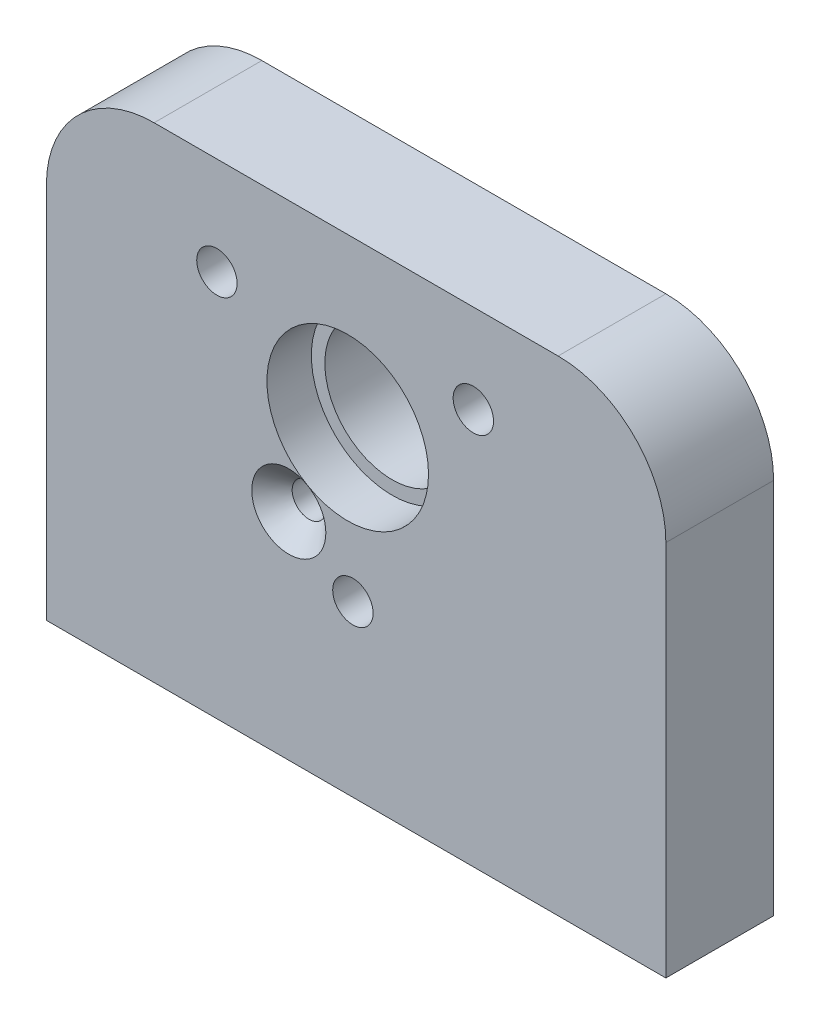
SolidWorks part; units mm, degrees
material "ABS"
ref_plane "Front Plane" through (0, 0, 0) normal (0, 0, 1) x (1, 0, 0)
ref_plane "Top Plane" through (0, 0, 0) normal (0, 1, 0) x (1, 0, 0)
ref_plane "Right Plane" through (0, 0, 0) normal (1, 0, 0) x (0, 0, -1)
ref_plane "Plane1" through (0, 0, 4.5) normal (0, 0, 1) x (1, 0, 0)
sketch "Sketch1" plane through (0, 0, 4.5) normal (0, 0, 1) x (1, 0, 0)
  line L0 (23, -18) -> (23, 18)
  line L1 (23, 18) -> (-23, 18)
  line L2 (-23, 18) -> (-23, -18)
  line L3 (-23, -18) -> (23, -18)
extrude "Boss-Extrude1" add sketch "Sketch1" against normal blind 8
ref_plane "Plane2" through (0, -2, 0) normal (0, 1, 0) x (1, 0, 0)
hole_wizard "Ø3.0mm Dowel Hole1" positions "Sketch6" profile "Sketch5" hole size "Ø3.0" standard "ANSI Metric"
sketch "Sketch6" plane through (0, -18, 0) normal (0, -1, 0) x (-1, 0, 0)
  line L0 (23, -4.5) -> (-23, -4.5) construction
  point P0 (0, -0.5)
  dimension "D1" = 4
sketch "Sketch5" plane through (0, -18, 0.5) normal (1, 0, 0) x (0, 0, -1)
  line L0 (0, 0) -> (0, 9.4013)
  line L1 (0, 9.4013) -> (1.5, 8.5)
  line L2 (1.5, 8.5) -> (1.5, 0)
  line L5 (1.5, 0) -> (0, 0)
  line L10 (0, 9.4013) -> (-1.5, 8.5) construction
  line L11 (0, -6.35) -> (0, 107.95) construction
  dimension "Hole Dia." = 3
  dimension "Hole Depth" = 8.5
  dimension "Drill Angle" = 118
hole_wizard "Ø4.0mm Dowel Hole1" positions "Sketch8" profile "Sketch7" hole size "Ø4.0" standard "ANSI Metric"
sketch "Sketch8" plane through (0, -18, 0) normal (0, -1, 0) x (-1, 0, 0)
  line L0 (23, -4.5) -> (-23, -4.5) construction
  point P0 (19, -0.5)
  point P1 (-19, -0.5)
  dimension "D1" = 4
sketch "Sketch7" plane through (-19, -18, 0.5) normal (1, 0, 0) x (0, 0, -1)
  line L0 (0, 0) -> (0, 8.7017)
  line L1 (0, 8.7017) -> (2, 7.5)
  line L2 (2, 7.5) -> (2, 0)
  line L5 (2, 0) -> (0, 0)
  line L10 (0, 8.7017) -> (-2, 7.5) construction
  line L11 (0, -6.35) -> (0, 107.95) construction
  dimension "Hole Dia." = 4
  dimension "Hole Depth" = 7.5
  dimension "Drill Angle" = 118
fillet "Fillet2" radius 8 2 edges at (23, 18, 0.5) (-23, 18, 0.5)
sketch "Sketch16" plane through (0, 0, -3.5) normal (0, 0, -1) x (-1, 0, 0)
  line L0 (23, -18) -> (-23, -18) construction
  line L1 (2.5, -4.5) -> (7.5, -4.5)
  line L2 (2.5, -4.5) -> (2.5, 0.5)
  line L3 (2.5, 0.5) -> (7.5, 0.5)
  line L4 (7.5, -4.5) -> (7.5, 0.5)
  line L5 (2.5, -4.5) -> (7.5, 0.5) construction
  line L6 (2.5, 0.5) -> (7.5, -4.5) construction
  line L9 (23, 10) -> (23, -18) construction
  point P0 (5, -2)
  dimension "D1" = 16
  dimension "D2" = 18
  dimension "D3" = 5
extrude "Cut-Extrude1" cut sketch "Sketch16" against normal blind 4.5
hole_wizard "CSK for M2.5 Flat Head Machine Screw1" positions "3DSketch1" profile "Sketch17" countersink size "M2.5" standard "ANSI Metric"
sketch3d "3DSketch1"
  line L0 (-23, -18, 4.5) -> (23, -18, 4.5) construction
  line L1 (-23, 10, 4.5) -> (-23, -18, 4.5) construction
  point P0 (-5, -2, 4.5)
  dimension "D1" = 16
  dimension "D2" = 18
sketch "Sketch17" plane through (-5, -2, 4.5) normal (1, 0, 0) x (0, -1, 0)
  line L0 (0, 0) -> (0, 10.2511)
  line L1 (0, 10.2511) -> (1.25, 9.5)
  line L2 (1.25, 9.5) -> (1.25, 1.5)
  line L3 (1.25, 1.5) -> (2.75, 0)
  line L5 (2.75, 0) -> (0, 0)
  line L6 (-1.25, 1.5) -> (-2.75, 0) construction
  line L10 (0, 10.2511) -> (-1.25, 9.5) construction
  line L11 (0, -6.35) -> (0, 107.95) construction
  dimension "Hole Dia." = 2.5
  dimension "Hole Depth" = 9.5
  dimension "Near C'Sink Dia." = 5.5
  dimension "Near C'Sink Angle" = 90
  dimension "Drill Angle" = 118
hole_wizard "Hole1" positions "Sketch12" profile "Sketch11" legacy end condition through all
sketch "Sketch12" plane through (0, 0, 4.5) normal (0, 0, 1) x (1, 0, 0)
  line L0 (-5, -2) -> (-0.625, 5.5777) construction
  line L1 (-0.625, 5.5777) -> (-0.625, -18) construction
  line L2 (-23, -18) -> (23, -18) construction
  point P0 (-0.625, 5.5777)
  dimension "D1" = 8.75
  dimension "D2" = 30
sketch "Sketch11" plane through (-0.625, 5.5777, 4.5) normal (1, 0, 0) x (0, -1, 0)
  line L0 (0, 0) -> (0, 8)
  line L1 (0, 8) -> (5, 8)
  line L2 (5, 8) -> (5, 3.3)
  line L3 (5, 3.3) -> (6, 3.3)
  line L4 (6, 3.3) -> (6, 0)
  line L5 (6, 0) -> (0, 0)
  line L6 (0, 110) -> (0, -10) construction
  dimension "Diameter" = 10
  dimension "Depth" = 8
  dimension "C-Bore Diameter" = 12
  dimension "C-Bore Depth" = 3.3
hole_wizard "Ø3.0 (3) Diameter Hole1" positions "Sketch10" profile "Sketch9" hole size "Ø3.0" standard "ANSI Metric" end condition through all
sketch "Sketch10" plane through (0, 0, -3.5) normal (0, 0, -1) x (-1, 0, 0)
  line L1 (10.3374, 10.7419) -> (-8.7035, 11.4068) construction
  line L2 (-8.7035, 11.4068) -> (0.2411, -5.4156) construction
  line L3 (0.2411, -5.4156) -> (10.3374, 10.7419) construction
  line L4 (0.625, 5.5777) -> (0.2411, -5.4156) construction
  line L7 (0.625, 5.5777) -> (0.625, -18) construction
  line L8 (23, -18) -> (-23, -18) construction
  circle A0 centre (0.625, 5.5777) radius 5.5 construction
  point P30 (-8.7035, 11.4068)
  point P33 (10.3374, 10.7419)
  point P36 (0.2411, -5.4156)
  dimension "D1" = 2
sketch "Sketch9" plane through (8.7035, 11.4068, -3.5) normal (1, 0, 0) x (0, 1, 0)
  line L0 (0, 0) -> (0, 8)
  line L1 (0, 8) -> (1.5, 8)
  line L2 (1.5, 8) -> (1.5, 0)
  line L5 (1.5, 0) -> (0, 0)
  line L11 (0, -6.35) -> (0, 107.95) construction
  dimension "Thru Hole Dia." = 3
  dimension "Thru Hole Depth" = 8
fillet "Fillet3" radius 1 4 edges at (-2.5, -4.5, -1.25) (-7.5, -4.5, -1.25) (-7.5, 0.5, -1.25) (-2.5, 0.5, -1.25)
sketch "Sketch18" plane through (0, 0, -3.5) normal (0, 0, -1) x (-1, 0, 0)
  line L0 (0.625, 18) -> (0.625, -18) construction
  line L1 (6.125, 15.104) -> (-10.375, 5.5777) construction
  line L2 (-10.375, 5.5777) -> (6.125, -3.9486) construction
  line L3 (6.125, -3.9486) -> (6.125, 15.104) construction
  line L4 (-15, 18) -> (15, 18) construction
  line L5 (23, -18) -> (-23, -18) construction
  line L6 (0.625, 5.5777) -> (6.125, -3.9486) construction
  circle A0 centre (0.625, 5.5777) radius 5.5 construction
  dimension "D1" = 11
  dimension "D2" = 30
sketch "Sketch20" plane through (0, 0, -3.5) normal (0, 0, -1) x (-1, 0, 0)
  line L1 (14.3789, 10.7419) -> (12.3581, 14.2419)
  line L2 (12.3581, 14.2419) -> (8.3167, 14.2419)
  line L3 (8.3167, 14.2419) -> (6.296, 10.7419)
  line L4 (6.296, 10.7419) -> (8.3167, 7.2419)
  line L5 (8.3167, 7.2419) -> (12.3581, 7.2419)
  line L6 (12.3581, 7.2419) -> (14.3789, 10.7419)
  circle A0 centre (10.3374, 10.7419) radius 3.5 construction
  point P1 (10.3374, 7.2419)
  dimension "D1" = 7
extrude "Cut-Extrude2" cut sketch "Sketch20" against normal blind 4
